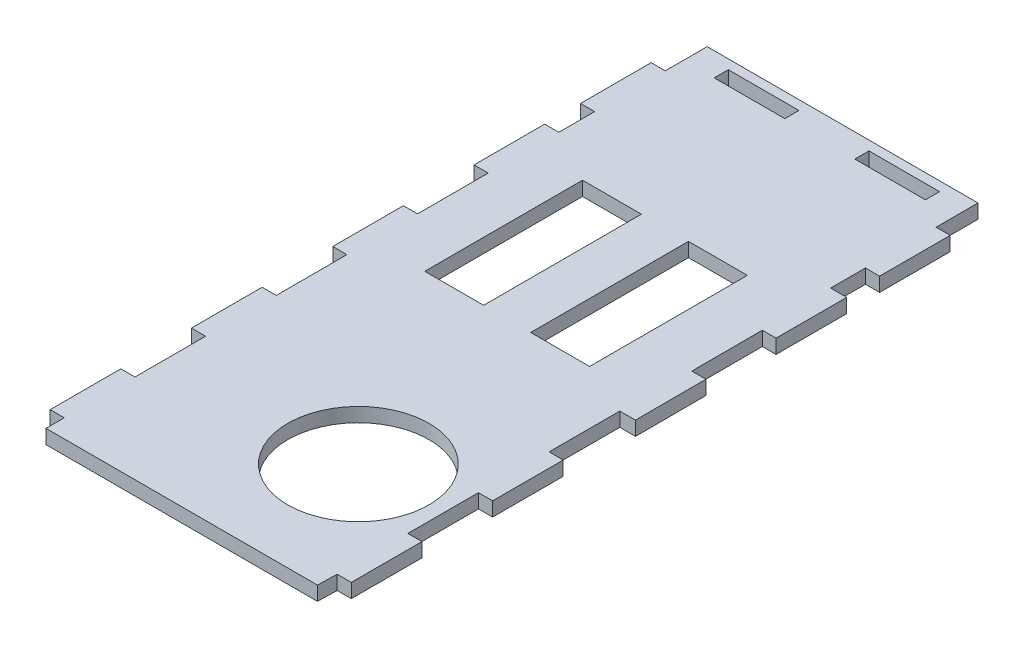
SolidWorks part; units mm, degrees
ref_plane "Спереди" through (0, 0, 0) normal (0, 0, 1) x (1, 0, 0)
ref_plane "Сверху" through (0, 0, 0) normal (0, 1, 0) x (1, 0, 0)
ref_plane "Справа" through (0, 0, 0) normal (1, 0, 0) x (0, 0, -1)
sketch "Эскиз1" plane through (0, 0, 0) normal (0, 1, 0) x (1, 0, 0)
  line L0 (-63.5, -120.2191) -> (-57.5, -120.2191)
  line L1 (-57.5, 152.7809) -> (57.5, 152.7809)
  line L2 (-63.5, 89.7809) -> (-63.5, 59.7809)
  line L3 (-57.5, -137.9871) -> (57.5, -137.9871)
  line L4 (-44.5343, -133.9871) -> (-14.5343, -133.9871)
  line L5 (15.1728, -133.9871) -> (45.1728, -133.9871)
  line L6 (-57.5, 89.7809) -> (-57.5, 104.9828)
  line L7 (-63.0343, -0.2191) -> (-57.5, -0.2191)
  line L8 (-57.5, -90.2191) -> (-63.5, -90.2191)
  line L9 (-57.5, -120.2191) -> (-57.5, -137.9871)
  line L10 (-63.0343, -60.2191) -> (-57.5, -60.2191)
  line L11 (-57.5, -90.2191) -> (-57.5, -60.2191)
  line L12 (-63.5, -90.2191) -> (-63.5, -120.2191)
  line L13 (45.1728, -133.9871) -> (15.1728, -133.9871)
  line L14 (57.5, 90.1915) -> (57.5, 104.9828)
  line L15 (-57.5, -30.2191) -> (-57.5, -0.2191)
  line L16 (-57.5, -30.2191) -> (-63.5, -30.2191)
  line L17 (-63.5, -30.2191) -> (-63.5, -60.2191)
  line L18 (-63.5, -60.2191) -> (-57.5, -60.2191)
  line L19 (-63.5, 29.7809) -> (-63.5, -0.2191)
  line L20 (-63.0343, 59.7809) -> (-57.5, 59.7809)
  line L21 (-57.5, 29.7809) -> (-57.5, 59.7809)
  line L22 (-57.5, 29.7809) -> (-63.5, 29.7809)
  line L23 (-63.5, 29.7809) -> (-63.5, -0.2191)
  line L24 (-63.5, -0.2191) -> (-57.5, -0.2191)
  line L25 (64.3313, 60.1914) -> (58.5025, 60.1935)
  line L26 (64.3319, 90.1914) -> (64.3313, 60.1914)
  line L27 (-57.5, 89.7809) -> (-57.5, 104.9828)
  line L28 (-57.5, 89.7809) -> (-63.5, 89.7809)
  line L29 (-63.5, 89.7809) -> (-63.5, 59.7809)
  line L30 (-63.5, 59.7809) -> (-57.5, 59.7809)
  line L31 (57.5, 90.1915) -> (64.3319, 90.1914)
  line L32 (-57.5, -60.2191) -> (-57.5, -77.9871) [skipped]
  line L33 (-57.5, -0.2191) -> (-57.5, -17.9871) [skipped]
  line L34 (-57.5, 59.7809) -> (-57.5, 42.0129) [skipped]
  line L35 (-63.0343, 119.7809) -> (-57.5, 119.7809) [skipped]
  line L36 (64.6117, 0.2045) -> (57.9657, 0.1917)
  line L37 (64.5571, 30.2044) -> (64.6117, 0.2045)
  line L38 (58.5571, 30.1935) -> (64.5571, 30.2044)
  line L39 (58.5571, 30.1935) -> (58.5025, 60.1935)
  line L40 (64.3313, 60.1914) -> (58.5025, 60.1935)
  line L41 (64.5571, 30.2044) -> (64.6117, 0.2045)
  line L42 (63.9657, -59.8083) -> (57.9657, -59.8083)
  line L43 (63.9657, -29.8083) -> (63.9657, -59.8083)
  line L44 (57.9657, -29.8083) -> (63.9657, -29.8083)
  line L45 (57.9657, -29.8083) -> (57.9657, 0.1917)
  line L46 (63.9657, -89.8083) -> (63.9657, -119.8083)
  line L47 (57.9657, -89.8083) -> (57.9657, -59.8083)
  line L48 (63.9657, -59.8083) -> (57.9657, -59.8083)
  line L49 (57.9657, -119.8083) -> (57.5, -137.9871)
  line L50 (57.9657, -89.8083) -> (63.9657, -89.8083)
  line L51 (64.6117, 0.2045) -> (57.9657, 0.1917)
  line L52 (64.3319, 90.1914) -> (64.3313, 60.1914)
  line L53 (63.9657, -119.8083) -> (57.9657, -119.8083)
  line L54 (-44.5343, -133.9871) -> (-14.5343, -133.9871)
  line L55 (-44.5343, -133.9871) -> (-44.5343, -127.9871)
  line L56 (-57.5, -127.9871) -> (-14.5343, -127.9871)
  line L57 (-14.5343, -133.9871) -> (-14.5343, -127.9871)
  line L58 (45.1728, -133.9871) -> (45.1728, -127.9871)
  line L59 (57.7562, -127.9871) -> (-14.5343, -127.9871)
  line L60 (15.1728, -133.9871) -> (15.1728, -127.9871)
  line L61 (-57.5, 104.9828) -> (-63.5, 104.9828)
  line L62 (-63.5, 104.9828) -> (-63.5, 134.9828)
  line L63 (-34.8502, 77.1917) -> (-9.8502, 77.1917)
  line L64 (-34.8502, 77.1917) -> (-34.8502, 10.1917)
  line L65 (-34.8502, 10.1917) -> (-9.8502, 10.1917)
  line L66 (-9.8502, 77.1917) -> (-9.8502, 10.1917)
  line L67 (-63.5, 134.9828) -> (-57.5, 134.9828)
  line L68 (10.1498, 77.1917) -> (35.1498, 77.1917)
  line L69 (10.1498, 77.1917) -> (10.1498, 10.1917)
  line L70 (10.1498, 10.1917) -> (35.1498, 10.1917)
  line L71 (35.1498, 77.1917) -> (35.1498, 10.1917)
  line L72 (-57.5, 134.9828) -> (-57.5, 152.7809)
  line L73 (0, 0) -> (0, 363.6353) construction
  line L74 (57.5, 134.9828) -> (57.5, 152.7809)
  line L75 (63.5, 134.9828) -> (57.5, 134.9828)
  line L76 (57.5, 104.9828) -> (63.5, 104.9828)
  line L77 (57.5, 89.7809) -> (57.5, 104.9828)
  line L78 (63.5, 104.9828) -> (63.5, 134.9828)
  line L79 (57.5, 134.9828) -> (57.5, 152.7809)
  line L80 (-44.5343, 142.7809) -> (-14.5343, 142.7809)
  line L82 (15.1728, 142.7809) -> (45.1728, 142.7809)
  line L83 (15.1728, 142.7809) -> (45.1728, 142.7809)
  line L84 (15.1728, 142.7809) -> (45.1728, 142.7809)
  line L85 (-44.5343, 146.7809) -> (-44.5343, 148.7809)
  line L86 (-57.5, 152.7809) -> (-14.5343, 152.7809)
  line L87 (-14.5343, 146.7809) -> (-14.5343, 148.7809)
  line L88 (45.1728, 146.7809) -> (45.1728, 148.7809)
  line L89 (57.5, 152.7809) -> (-14.5343, 152.7809)
  line L90 (15.1728, 146.7809) -> (15.1728, 148.7809)
  line L91 (-92.9416, 147.7809) -> (64.5571, 147.7809) construction
  line L92 (-57.5, 152.7809) -> (57.5, 152.7809)
  line L93 (-44.5343, 142.7809) -> (-14.5343, 142.7809)
  line L94 (-57.5, 152.7809) -> (57.5, 152.7809)
  line L95 (-44.5343, 142.7809) -> (-14.5343, 142.7809)
  line L96 (15.1728, 148.7809) -> (15.1728, 142.7809)
  line L97 (45.1728, 142.7809) -> (15.1728, 142.7809)
  line L98 (45.1728, 148.7809) -> (45.1728, 142.7809)
  line L99 (-14.5343, 148.7809) -> (-14.5343, 142.7809)
  line L100 (-44.5343, 142.7809) -> (-14.5343, 142.7809)
  line L101 (-44.5343, 148.7809) -> (-44.5343, 142.7809)
  line L102 (-44.5343, 148.7809) -> (-14.5343, 148.7809)
  line L103 (45.1728, 148.7809) -> (15.1728, 148.7809)
  line L104 (15.1728, 148.7809) -> (45.1728, 148.7809)
  line L105 (-44.5343, 148.7809) -> (-14.5343, 148.7809)
  line L106 (-57.5, 152.7809) -> (57.5, 152.7809)
  line L107 (-44.5343, 142.7809) -> (-14.5343, 142.7809)
  line L108 (15.1728, 142.7809) -> (45.1728, 142.7809)
  circle A0 centre (21.9657, -74.8083) radius 30
  point P0 (0, 0)
  dimension "D13" = 36
  dimension "D1" = 6
  dimension "D2" = 4
  dimension "D3" = 6
  dimension "D4" = 30
  dimension "D5" = 4
  dimension "D6" = 115
  dimension "D7" = 115
  dimension "D8" = 30
  dimension "D9" = 6
  dimension "D10" = 30
  dimension "D11" = 6
  dimension "D12" = 25
  dimension "D14" = 67
  dimension "D15" = 25
  dimension "D16" = 63
  dimension "D17" = 30
  dimension "D18" = 6
extrude "Бобышка-Вытянуть1" add sketch "Эскиз1" along normal blind 6 contours L76 L78 L75 L74 L1 L72 L67 L62 L61 L6 L28 L2 L30 L20 L21 L22 L19 L24 L7 L15 L16 L17 L18 L10 L11 L8 L12 L0 L9 L56 L59 L49 L53 L46 L50 L47 L42 L43 L44 L45 L36 L37 L38 L39 L25 L26 L31
